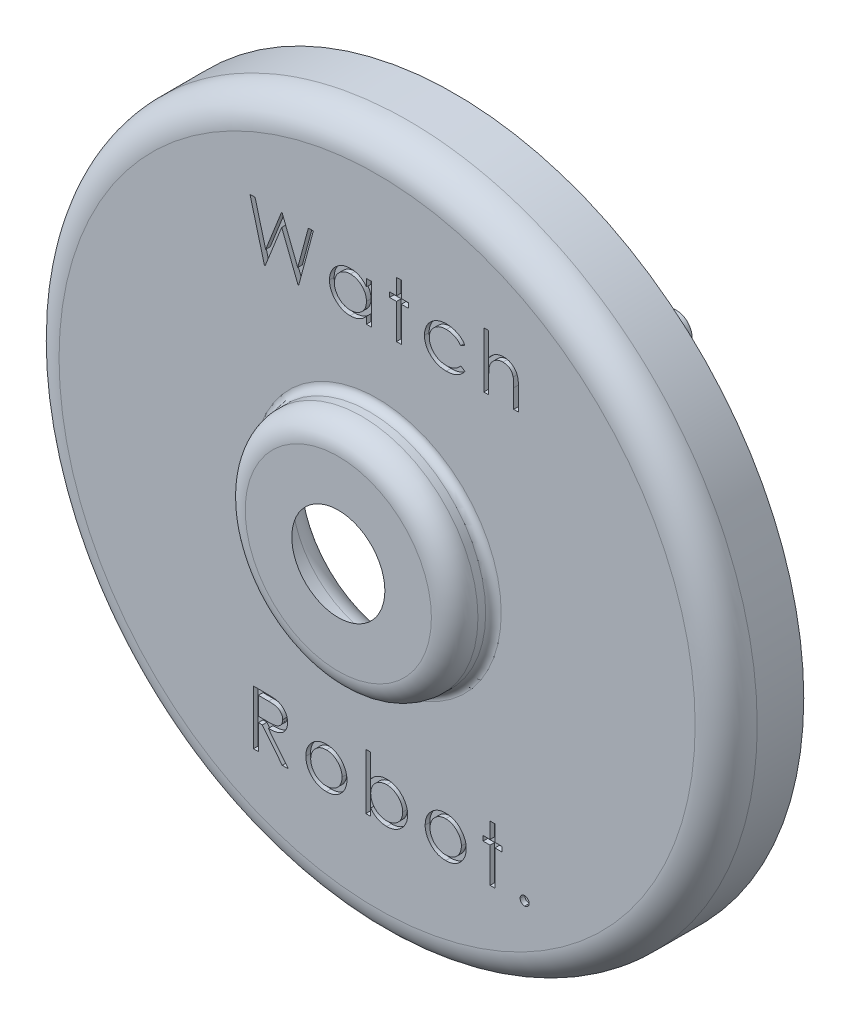
SolidWorks part; units mm, degrees
material "ABS"
ref_plane "Plan de face" through (0, 0, 0) normal (0, 0, 1) x (1, 0, 0)
ref_plane "Plan de dessus" through (0, 0, 0) normal (0, 1, 0) x (1, 0, 0)
ref_plane "Plan de droite" through (0, 0, 0) normal (1, 0, 0) x (0, 0, -1)
sketch "Esquisse1" plane through (0, 0, 0) normal (0, 0, 1) x (1, 0, 0)
  circle A0 centre (0.2935, -2.7779) radius 20
  circle A1 centre (0.2935, -2.7779) radius 22.5
  circle A4 centre (0.2935, -2.7779) radius 1.45 construction
  dimension "D1" = 40
  dimension "D2" = 45
extrude "Boss.-Extru.1" add sketch "Esquisse1" against normal blind 2.5
sketch "Esquisse4" plane through (0, 0, 0) normal (0, 0, 1) x (1, 0, 0)
  circle A0 centre (0.2935, -2.7779) radius 20
  circle A1 centre (0.2935, -2.7779) radius 22.5
  dimension "D1" = 40
  dimension "D2" = 45
extrude "Boss.-Extru.2" add sketch "Esquisse4" along normal blind 0.5
ref_plane "Plan1" through (0, -2.78, 0) normal (0, 1, 0) x (-1, 0, 0)
sketch "Esquisse5" plane through (0, -2.78, 0) normal (0, 1, 0) x (-1, 0, 0)
  line L0 (-0.2935, 19.4885) -> (-0.2935, -10.0724) construction
  line L1 (-22.7935, 0.5) -> (-22.7935, -2.5) construction
  line L2 (-3.2935, 5) -> (-6.2935, 5)
  line L4 (-7.7935, 3.5) -> (-7.7935, 3)
  line L5 (-8.2935, 2.5) -> (-20.7935, 2.5)
  line L7 (22.2065, 0.5) -> (-22.7935, 0.5) construction
  line L8 (-22.7935, 0.5) -> (-20.2935, 0.5)
  line L9 (19.7065, 0.5) -> (-20.2935, 0.5) construction
  line L11 (-19.7935, 1) -> (-7.2935, 1)
  line L12 (-5.7935, 2.5) -> (-5.7935, 3.5)
  line L13 (-3.2935, 5) -> (-5.7935, 3.5)
  arc A0 (-22.7935, 0.5) -> (-20.7935, 2.5) centre (-20.7935, 0.5) cw
  arc A1 (-20.2935, 0.5) -> (-19.7935, 1) centre (-19.7935, 0.5) cw
  arc A4 (-7.7935, 3.5) -> (-6.2935, 5) centre (-6.2935, 3.5) cw
  arc A6 (-7.2935, 1) -> (-5.7935, 2.5) centre (-7.2935, 2.5) ccw
  arc A7 (-7.7935, 3) -> (-8.2935, 2.5) centre (-8.2935, 3) cw
  point P30 (-7.7935, 5)
  point P37 (-7.7935, 5)
  dimension "D13" = 1.5
  dimension "D17" = 1.5
  dimension "D4" = 1.5
  dimension "D8" = 2
  dimension "D11" = 0.5
  dimension "D12" = 0.5
  dimension "D1" = 22.5
  dimension "D2" = 22.5
  dimension "D3" = 1.5
  dimension "D5" = 2.5
  dimension "D6" = 3
  dimension "D7" = 2
  dimension "D9" = 2.5
revolve "Révolution1" add sketch "Esquisse5" angle 360 about L0
sketch "Esquisse6" plane through (0, 0, 2.5) normal (0, 0, 1) x (1, 0, 0)
  text T0 "  Watch \r\n \r\n\r\n\r\n  Robot." font "Century Gothic" height 3.5
  dimension "D1" = 9
  dimension "D2" = 12
extrude "Enlèv. mat.-Extru.1" cut sketch "Esquisse6" against normal blind 0.3
sketch "Esquisse7" plane through (0, 0, 1) normal (0, 0, -1) x (-1, 0, 0)
  circle A0 centre (-10.7935, 9.9721) radius 1
  circle A1 centre (10.2065, 9.9721) radius 1
  circle A2 centre (10.2065, -2.5279) radius 1
  circle A3 centre (-10.7935, -2.5279) radius 1
  dimension "D1" = 2
  dimension "D2" = 2
  dimension "D3" = 2
  dimension "D4" = 2
  dimension "D5" = 12.5
  dimension "D6" = 21
extrude "Boss.-Extru.3" add sketch "Esquisse7" along normal blind 7.3
sketch "Esquisse8" plane through (0, 0, 1) normal (0, 0, -1) x (-1, 0, 0)
  circle A0 centre (-10.7935, 9.9721) radius 1.5
  circle A1 centre (10.2065, 9.9721) radius 1.5
  circle A2 centre (10.2065, -2.5279) radius 1.5
  circle A3 centre (-10.7935, -2.5279) radius 1.5
  dimension "D1" = 3
  dimension "D2" = 3
  dimension "D3" = 3
  dimension "D4" = 3
extrude "Boss.-Extru.4" add sketch "Esquisse8" along normal blind 1.7
